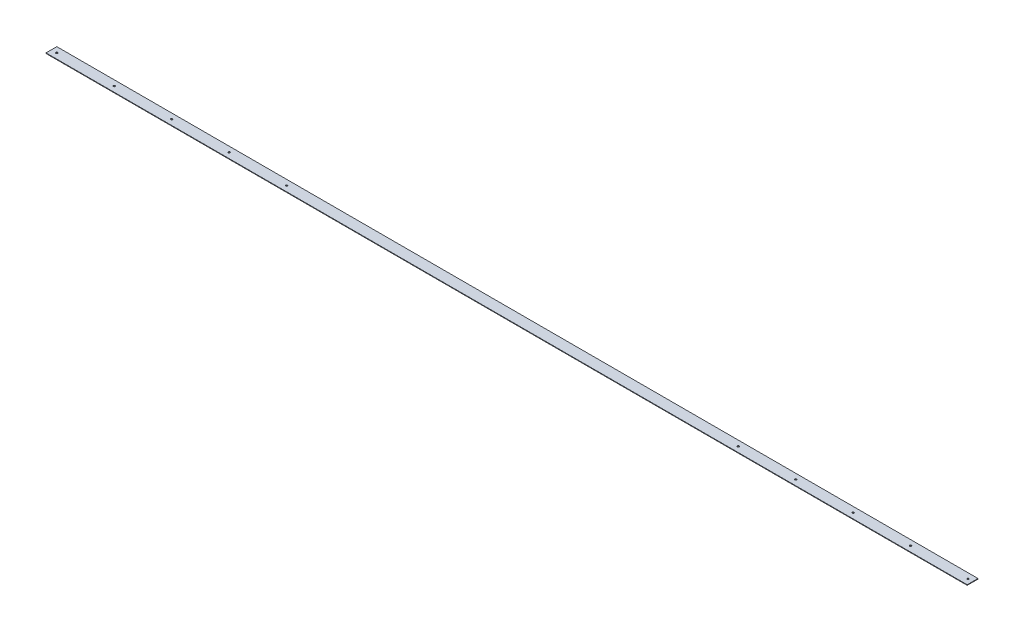
SolidWorks part; units mm, degrees
material "5052-H32"
ref_plane "Front Plane" through (0, 0, 0) normal (0, 0, 1) x (1, 0, 0)
ref_plane "Top Plane" through (0, 0, 0) normal (0, 1, 0) x (1, 0, 0)
ref_plane "Right Plane" through (0, 0, 0) normal (1, 0, 0) x (0, 0, -1)
sketch "Sketch1" plane through (0, 0, 0) normal (0, 1, 0) x (1, 0, 0)
  line L1 (1704.25, -20) -> (-1704.25, -20)
  line L2 (1704.25, -20) -> (1704.25, 20)
  line L3 (1704.25, 20) -> (-1704.25, 20)
  line L4 (-1704.25, -20) -> (-1704.25, 20)
  line L5 (1704.25, -20) -> (-1704.25, 20) construction
  line L6 (1704.25, 20) -> (-1704.25, -20) construction
  point P0 (0, 0)
  dimension "D1" = 40
  dimension "D2" = 3408.5
extrude "Boss-Extrude1" add sketch "Sketch1" along normal blind 2
sketch "Sketch2" plane through (0, 2, 0) normal (0, 1, 0) x (1, 0, 0)
  line L0 (-1704.25, -20) -> (1704.25, -20) construction
  line L1 (-1704.25, 20) -> (-1704.25, -20) construction
  line L2 (1704.25, -20) -> (1704.25, 20) construction
  circle A0 centre (-1684.25, 0) radius 3.4
  circle A1 centre (-1471.75, 0) radius 3.4
  circle A2 centre (-1259.25, 0) radius 3.4
  circle A3 centre (-1046.75, 0) radius 3.4
  circle A4 centre (-834.25, 0) radius 3.4
  circle A5 centre (1687.25, 0) radius 3.4
  circle A6 centre (1474.75, 0) radius 3.4
  circle A7 centre (1262.25, 0) radius 3.4
  circle A8 centre (1049.75, 0) radius 3.4
  circle A9 centre (837.25, 0) radius 3.4
  dimension "D1" = 6.8
  dimension "D5" = 212.5
  dimension "D8" = 5
  dimension "D2" = 20
  dimension "D3" = 20
  dimension "D6" = 17
  dimension "D7" = 20
  dimension "D9" = 212.5
  dimension "D4" = 5
extrude "Cut-Extrude1" cut sketch "Sketch2" against normal blind 10
